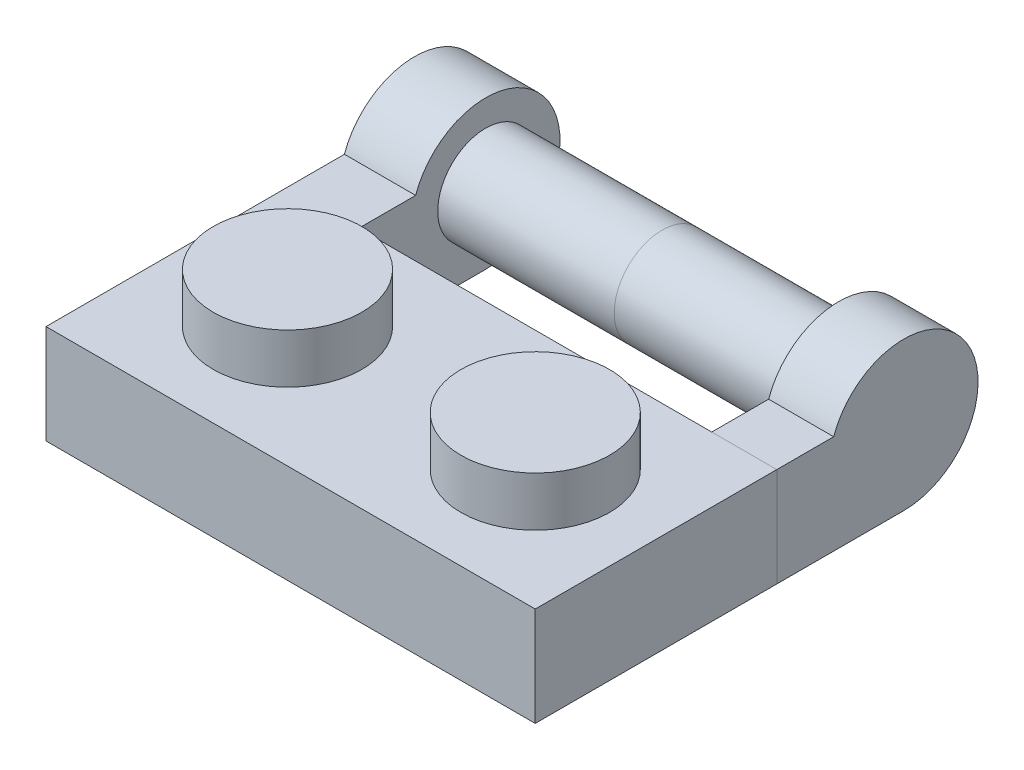
SolidWorks part; units mm, degrees
material "ABS"
ref_plane "Front Plane" through (0, 0, 0) normal (0, 0, 1) x (1, 0, 0)
ref_plane "Top Plane" through (0, 0, 0) normal (0, 1, 0) x (1, 0, 0)
ref_plane "Right Plane" through (0, 0, 0) normal (1, 0, 0) x (0, 0, -1)
sketch "Sketch1" plane through (0, 0, 0) normal (0, 0, 1) x (1, 0, 0)
  line L1 (0, 0) -> (15.8, 0)
  line L2 (0, 0) -> (0, 3.2)
  line L3 (0, 3.2) -> (15.8, 3.2)
  line L4 (15.8, 0) -> (15.8, 3.2)
  line L5 (0, 0) -> (15.8, 3.2) construction
  line L6 (0, 3.2) -> (15.8, 0) construction
  point P4 (7.9, 1.6)
  dimension "D1" = 15.8
  dimension "D2" = 3.2
extrude "Boss-Extrude1" add sketch "Sketch1" against normal blind 7.8
sketch "Sketch2" plane through (0, 3.2, 0) normal (0, 1, 0) x (1, 0, 0)
  line L0 (15.8, 0) -> (0, 0) construction
  circle A0 centre (3.9, 3.9) radius 2.4
  dimension "D1" = 4.8
  dimension "D2" = 3.9
  dimension "D3" = 3.9
extrude "Boss-Extrude2" add sketch "Sketch2" along normal blind 1.6
pattern_linear "LPattern1" count 2 spacing 8 along (0, 0, 1) count 4 spacing 8 along (1, 0, 0) of "Boss-Extrude2"
shell "Shell1" thickness 1.2
sketch "Sketch3" plane through (0, 2, 0) normal (0, -1, 0) x (1, 0, 0)
  line L0 (0, 0) -> (15.8, 0) construction
  line L1 (0, -7.8) -> (0, 0) construction
  circle A0 centre (7.9, -3.9) radius 1.5
  circle A1 centre (7.9, -3.9) radius 0.6
  dimension "D1" = 3
  dimension "D2" = 1.2
  dimension "D3" = 3.9
  dimension "D4" = 7.9
extrude "Boss-Extrude3" add sketch "Sketch3" along normal offset from surface (1.8 mm away) 0.2 up to face at (7.9, 0, -3.9)
sketch "Sketch4" plane through (15.8, 0, 0) normal (1, 0, 0) x (0, 0, -1)
  line L0 (7.8, 3.2) -> (9.6373, 3.2)
  line L2 (11.9, 0) -> (7.8, 0)
  line L3 (7.8, 0) -> (7.8, 3.2)
  line L4 (0, 0) -> (0, 3.2) construction
  arc A0 (11.9, 0) -> (9.6373, 3.2) centre (11.9, 2.4) ccw
  dimension "D1" = 4.8
  dimension "D2" = 11.9
extrude "Boss-Extrude4" add sketch "Sketch4" against normal blind 2.1 separate body
ref_point "Point1"
ref_plane "Plane1" through (8, 0, 0) normal (1, 0, 0) x (0, 0, -1)
sketch "Sketch5" plane through (13.7, 0, 0) normal (-1, 0, 0) x (0, 0, 1)
  circle A0 centre (-11.9, 2.4) radius 1.55
  dimension "D1" = 3.1
extrude "Boss-Extrude5" add sketch "Sketch5" along normal up to surface (5.7 mm away) up to plane "Plane1"
mirror "Mirror2" about plane through (8, 0, 0) normal (1, 0, 0) of bodies 109
sketch "Sketch6" plane through (0.2, 0, 0) normal (-1, 0, 0) x (0, 0, 1)
  line L3 (-7.8, 0) -> (-7.8, 3.2)
  line L4 (-7.8, 3.2) -> (-9.6373, 3.2)
  line L5 (-11.9, 0) -> (-7.8, 0)
  line L6 (-7.8, 0) -> (-7.8, 3.2)
  line L7 (-7.8, 3.2) -> (-9.6373, 3.2)
  line L8 (-11.9, 0) -> (-7.8, 0)
  arc A1 (-9.6373, 3.2) -> (-11.9, 0) centre (-11.9, 2.4) ccw
  arc A2 (-9.6373, 3.2) -> (-11.9, 0) centre (-11.9, 2.4) ccw
  dimension "D1" = 0
extrude "Boss-Extrude6" add sketch "Sketch6" along normal up to surface (0.2 mm away) up to face at (0, 1.6, -3.9)
